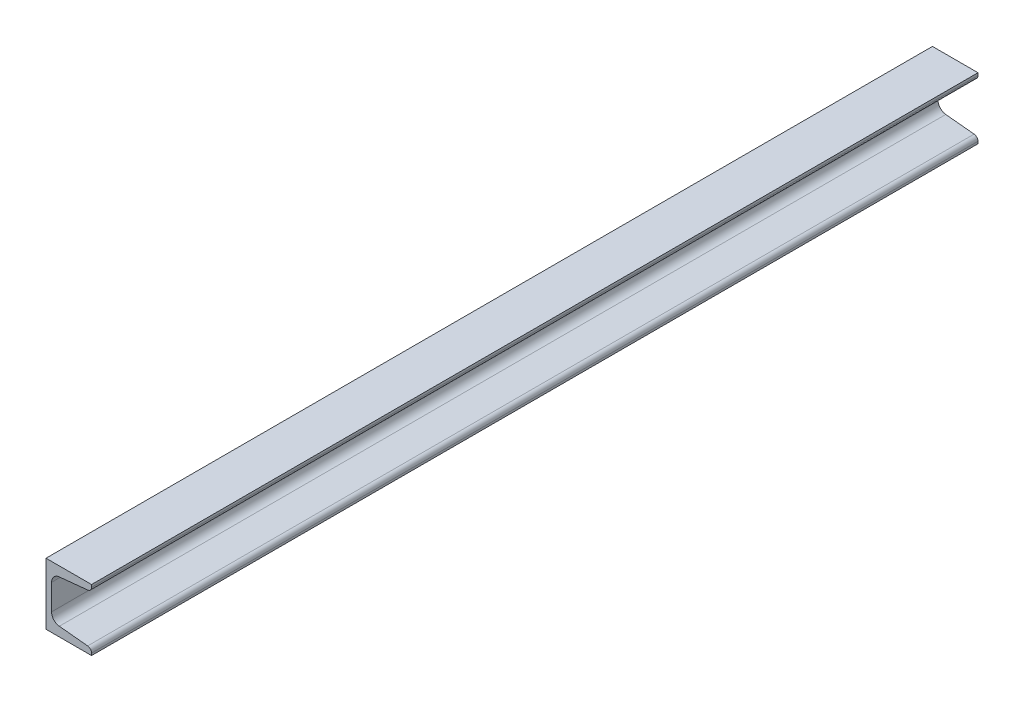
SolidWorks part; units mm, degrees
ref_plane "前视基准面" through (0, 0, 0) normal (0, 0, 1) x (1, 0, 0)
ref_plane "上视基准面" through (0, 0, 0) normal (0, 1, 0) x (1, 0, 0)
ref_plane "右视基准面" through (0, 0, 0) normal (1, 0, 0) x (0, 0, -1)
sketch "草图1" plane through (0, 0, 0) normal (0, 0, 1) x (1, 0, 0)
  line L0 (0, 0) -> (0, 50)
  line L1 (0, 0) -> (37, 0)
  line L2 (-55.9537, 25) -> (55.9537, 25) construction
  line L3 (0, 50) -> (37, 50)
  line L4 (4.5, 14.5099) -> (4.5, 35.2876)
  line L5 (16.25, -10) -> (16.25, 60) construction
  line L6 (10.8035, 7.5447) -> (33.8483, 5.2402)
  line L7 (37, 0) -> (37, 1.7575)
  line L8 (10.8035, 42.2529) -> (33.8483, 44.5574)
  line L9 (37, 48.04) -> (37, 50)
  arc A0 (10.8035, 42.2529) -> (4.5, 35.2876) centre (11.5, 35.2876) ccw
  arc A1 (4.5, 14.5099) -> (10.8035, 7.5447) centre (11.5, 14.5099) ccw
  arc A2 (33.8483, 44.5574) -> (37, 48.04) centre (33.5, 48.04) ccw
  arc A3 (37, 1.7575) -> (33.8483, 5.2402) centre (33.5, 1.7575) ccw
  point P7 (0, 25)
  point P11 (4.5, 25)
  point P14 (16.25, 25)
  point P15 (16.25, 7)
  point P17 (16.25, 43)
  point P19 (16.25, 43)
  point P20 (16.25, 7)
  point P23 (16.25, 43)
  dimension "D5" = 7
  dimension "D6" = 7
  dimension "D7" = 3.5
  dimension "D8" = 3.5
  dimension "h" = 50
  dimension "b" = 37
  dimension "d" = 4.5
  dimension "D1" = 16.25
  dimension "D2" = 7
  dimension "D3" = 5.711
  dimension "D4" = 5.711
extrude "凸台-拉伸1" add sketch "草图1" along normal blind 720
equation "\"高度\"= 50"
equation "\"腿宽\"= 37"
equation "\"腰宽\"= 4.5"
equation "\"h@草图1\"= \"高度\""
equation "\"d@草图1\"= \"腰宽\""
equation "\"D1@草图1\"= ( \"腿宽\" - \"腰宽\" ) / 2"
equation "\"平均腿厚\"= 7"
equation "\"内圆弧半径\"= 7"
equation "\"腿端圆弧半径\"= 3.5"
equation "\"D2@草图1\"= \"平均腿厚\""
equation "\"斜度\"= atn ( 0.1 )"
equation "\"D3@草图1\"= \"斜度\""
equation "\"D4@草图1\"= \"斜度\""
equation "\"D5@草图1\"= \"内圆弧半径\""
equation "\"D6@草图1\"= \"内圆弧半径\""
equation "\"D8@草图1\"= \"腿端圆弧半径\""
equation "\"D7@草图1\"= \"腿端圆弧半径\""
equation "\"b@草图1\"= \"腿宽\""
